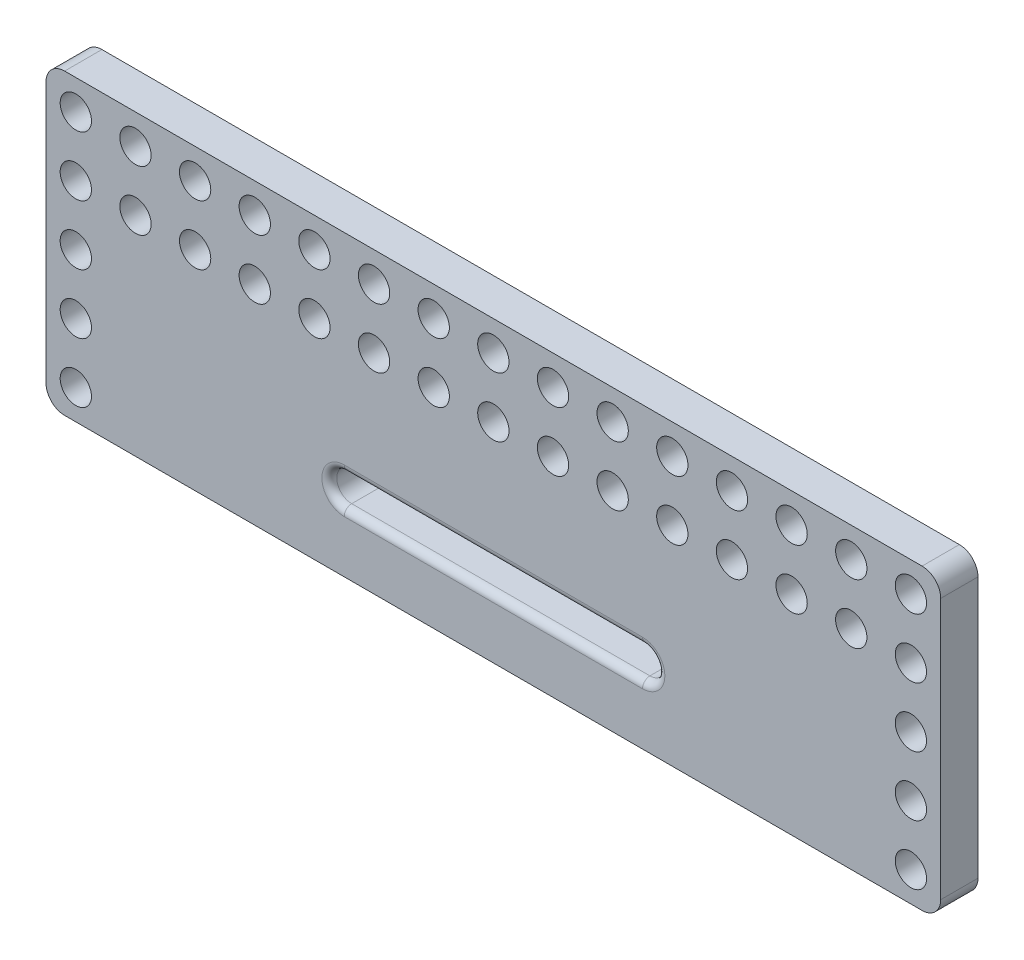
SolidWorks part; units mm, degrees
ref_plane "前视基准面" through (0, 0, 0) normal (0, 0, 1) x (1, 0, 0)
ref_plane "上视基准面" through (0, 0, 0) normal (0, 1, 0) x (1, 0, 0)
ref_plane "右视基准面" through (0, 0, 0) normal (1, 0, 0) x (0, 0, -1)
sketch "草图1" plane through (0, 0, 0) normal (0, 0, 1) x (1, 0, 0)
  line L0 (0, 0) -> (0, 30336.2514) construction
  line L3 (-60, -20) -> (60, -20)
  line L5 (-60, 20) -> (60, -20) construction
  line L6 (-60, -20) -> (60, 20) construction
  line L7 (20, -8) -> (-20, -8)
  line L8 (-20, -12) -> (20, -12)
  line L9 (-60, 20) -> (60, 20)
  line L13 (-56, -16) -> (-56, -8) construction
  line L14 (-56, 16) -> (-48, 16) construction
  line L36 (-60, 20) -> (-60, -20)
  line L37 (60, 20) -> (60, -20)
  arc A0 (-20, -8) -> (-20, -12) centre (-20, -10) ccw
  arc A1 (20, -8) -> (20, -12) centre (20, -10) cw
  circle A2 centre (-56, -16) radius 2.1
  circle A3 centre (-56, -8) radius 2.1
  circle A4 centre (-56, 0) radius 2.1
  circle A5 centre (-56, 8) radius 2.1
  circle A6 centre (-56, 16) radius 2.1
  circle A7 centre (56, 16) radius 2.1
  circle A8 centre (56, 8) radius 2.1
  circle A9 centre (56, 0) radius 2.1
  circle A10 centre (56, -16) radius 2.1
  circle A11 centre (56, -8) radius 2.1
  circle A12 centre (-48, 16) radius 2.1
  circle A13 centre (-48, 8) radius 2.1
  circle A14 centre (-40, 16) radius 2.1
  circle A15 centre (-40, 8) radius 2.1
  circle A16 centre (-32, 16) radius 2.1
  circle A17 centre (-32, 8) radius 2.1
  circle A18 centre (-24, 16) radius 2.1
  circle A19 centre (-24, 8) radius 2.1
  circle A20 centre (-16, 16) radius 2.1
  circle A21 centre (-16, 8) radius 2.1
  circle A22 centre (-8, 16) radius 2.1
  circle A23 centre (-8, 8) radius 2.1
  circle A24 centre (0, 16) radius 2.1
  circle A25 centre (0, 8) radius 2.1
  circle A26 centre (8, 16) radius 2.1
  circle A27 centre (8, 8) radius 2.1
  circle A28 centre (16, 16) radius 2.1
  circle A29 centre (16, 8) radius 2.1
  circle A30 centre (24, 16) radius 2.1
  circle A31 centre (24, 8) radius 2.1
  circle A32 centre (32, 16) radius 2.1
  circle A33 centre (32, 8) radius 2.1
  circle A34 centre (40, 16) radius 2.1
  circle A35 centre (40, 8) radius 2.1
  circle A36 centre (48, 16) radius 2.1
  circle A37 centre (48, 8) radius 2.1
  point P0 (0, 0)
  dimension "D1" = 20
  dimension "D5" = 2
  dimension "D7" = 4
  dimension "D8" = 4.2
  dimension "D13" = 4
  dimension "D2" = 120
  dimension "D3" = 40
  dimension "D4" = 10
  dimension "D6" = 40
  dimension "D10" = 8
  dimension "D12" = 8
  dimension "D9" = 5
  dimension "D11" = 14
extrude "凸台-拉伸1" add sketch "草图1" along normal blind 5
fillet "圆角1" radius 2.5 4 edges at (60, 20, 2.5) (60, -20, 2.5) (-60, -20, 2.5) (-60, 20, 2.5)
fillet "圆角2" radius 1 4 edges at (0, -8, 5) (-22, -10, 5) (0, -12, 5) (22, -10, 5)
